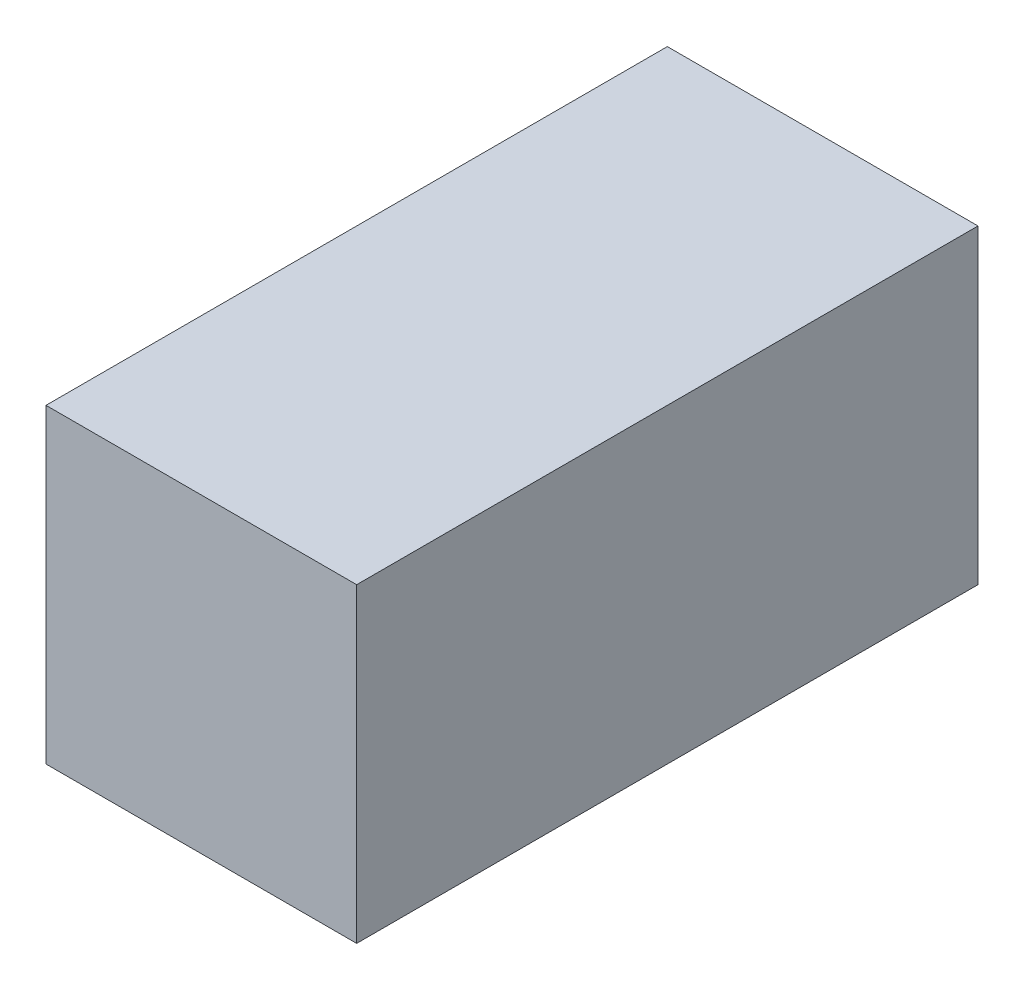
SolidWorks part; units mm, degrees
ref_plane "Front Plane" through (0, 0, 0) normal (0, 0, 1) x (1, 0, 0)
ref_plane "Top Plane" through (0, 0, 0) normal (0, 1, 0) x (1, 0, 0)
ref_plane "Right Plane" through (0, 0, 0) normal (1, 0, 0) x (0, 0, -1)
sketch "Sketch1" plane through (0, 0, 0) normal (0, 0, 1) x (1, 0, 0)
  line L1 (-75, -75) -> (75, -75)
  line L2 (-75, -75) -> (-75, 75)
  line L3 (-75, 75) -> (75, 75)
  line L4 (75, -75) -> (75, 75)
  line L5 (-75, -75) -> (75, 75) construction
  line L6 (-75, 75) -> (75, -75) construction
  point P0 (0, 0)
  dimension "D1" = 150
extrude "Boss-Extrude1" add sketch "Sketch1" along normal mid plane 300
